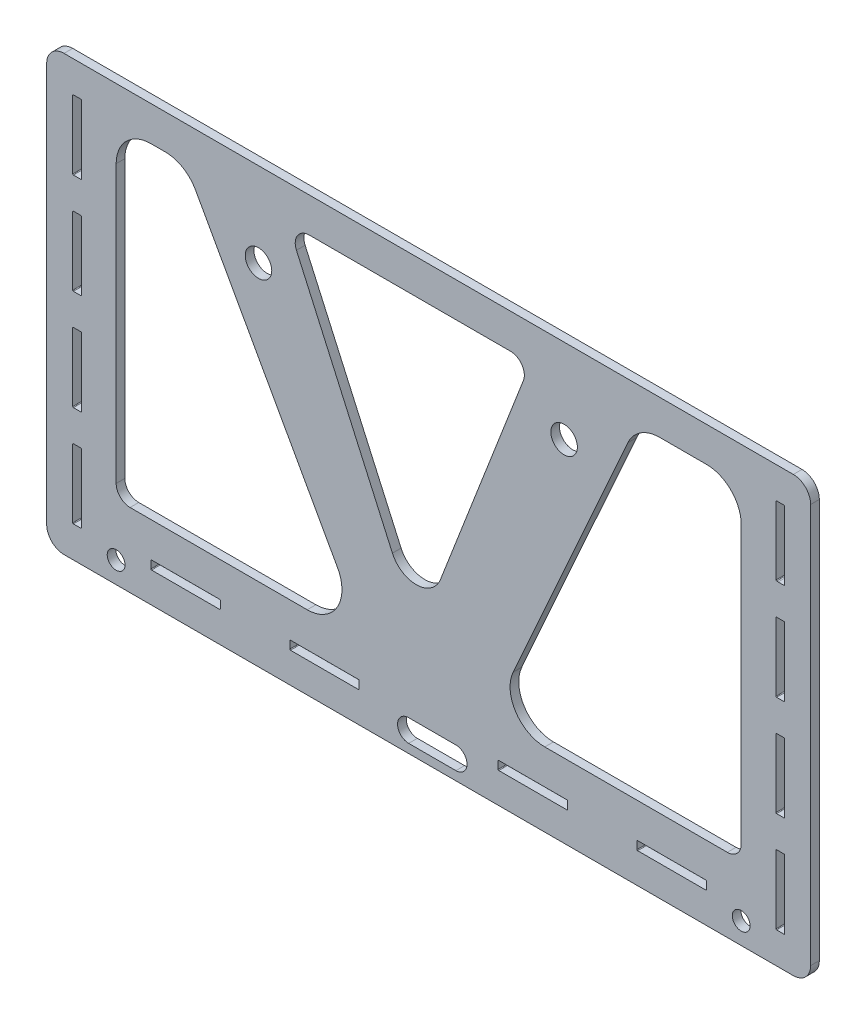
SolidWorks part; units mm, degrees
ref_plane "Front Plane" through (0, 0, 0) normal (0, 0, 1) x (1, 0, 0)
ref_plane "Top Plane" through (0, 0, 0) normal (0, 1, 0) x (1, 0, 0)
ref_plane "Right Plane" through (0, 0, 0) normal (1, 0, 0) x (0, 0, -1)
sketch "Model" plane through (0, 0, 0) normal (0, 0, 1) x (1, 0, 0)
  line L0 (402.4987, 280.7936) -> (432.8371, 358.964)
  line L1 (349.8266, 358.7257) -> (384.9258, 280.3469)
  line L2 (271.1967, 342.006) -> (271.1967, 366.898)
  line L3 (271.1967, 305.176) -> (271.1967, 330.068)
  line L4 (271.1967, 268.346) -> (271.1967, 293.238)
  line L5 (271.1967, 231.516) -> (271.1967, 256.408)
  line L6 (428.1012, 365.882) -> (354.463, 365.882)
  line L7 (270.9427, 367.152) -> (268.263, 367.152)
  line L8 (270.9427, 330.322) -> (268.263, 330.322)
  line L9 (270.9427, 293.492) -> (268.263, 293.492)
  line L10 (270.9427, 256.662) -> (268.263, 256.662)
  line L11 (283.8967, 251.9122) -> (283.8967, 353.182)
  line L12 (525.9968, 341.752) -> (525.4507, 341.752)
  line L13 (525.1967, 342.006) -> (525.1967, 366.898)
  line L14 (525.4507, 367.152) -> (528.1304, 367.152)
  line L15 (296.838, 234.1322) -> (321.73, 234.1322)
  line L16 (321.984, 233.8782) -> (321.984, 231.1985)
  line L17 (474.638, 234.1322) -> (499.53, 234.1322)
  line L18 (499.784, 233.8782) -> (499.784, 231.1985)
  line L19 (525.1967, 268.346) -> (525.1967, 293.238)
  line L20 (525.4507, 293.492) -> (528.1304, 293.492)
  line L21 (531.534, 378.582) -> (264.834, 378.582)
  line L22 (258.484, 372.232) -> (258.484, 226.182)
  line L23 (264.834, 219.832) -> (531.534, 219.832)
  line L24 (537.884, 226.182) -> (537.884, 372.232)
  line L25 (525.1967, 231.516) -> (525.1967, 256.408)
  line L26 (423.838, 234.1322) -> (448.73, 234.1322)
  line L27 (448.984, 233.8782) -> (448.984, 231.1985)
  line L28 (372.784, 233.8782) -> (372.784, 231.1985)
  line L29 (347.638, 234.1322) -> (372.53, 234.1322)
  line L30 (525.1967, 305.176) -> (525.1967, 330.068)
  line L31 (525.4507, 330.322) -> (528.1304, 330.322)
  line L32 (507.4167, 246.8322) -> (440.6634, 246.8322)
  line L33 (525.9968, 341.752) -> (528.1288, 341.7388)
  line L34 (528.1304, 231.262) -> (525.4507, 231.262)
  line L35 (528.3844, 231.516) -> (528.3844, 256.408)
  line L36 (528.3844, 341.9928) -> (528.3844, 366.898)
  line L37 (528.1304, 304.922) -> (525.4507, 304.922)
  line L38 (528.3844, 305.176) -> (528.3844, 330.068)
  line L39 (525.4507, 256.662) -> (528.1304, 256.662)
  line L40 (528.1304, 268.092) -> (525.4507, 268.092)
  line L41 (528.3844, 268.346) -> (528.3844, 293.238)
  line L42 (321.73, 230.9445) -> (296.838, 230.9445)
  line L43 (268.263, 341.752) -> (270.9427, 341.752)
  line L44 (268.009, 342.006) -> (268.009, 366.898)
  line L45 (268.263, 304.922) -> (270.9427, 304.922)
  line L46 (268.009, 305.176) -> (268.009, 330.068)
  line L47 (268.263, 268.092) -> (270.9427, 268.092)
  line L48 (268.009, 268.346) -> (268.009, 293.238)
  line L49 (268.263, 231.262) -> (270.9427, 231.262)
  line L50 (268.009, 231.516) -> (268.009, 256.408)
  line L51 (499.53, 230.9445) -> (474.638, 230.9445)
  line L52 (474.384, 231.1985) -> (474.384, 233.8782)
  line L53 (423.584, 231.1985) -> (423.584, 233.8782)
  line L54 (448.73, 230.9445) -> (423.838, 230.9445)
  line L55 (372.53, 230.9445) -> (347.638, 230.9445)
  line L56 (347.384, 231.1985) -> (347.384, 233.8782)
  line L57 (296.584, 231.1985) -> (296.584, 233.8782)
  line L58 (390.8786, 231.1985) -> (408.1506, 231.1985)
  line L59 (408.1506, 223.0705) -> (390.8786, 223.0705)
  line L60 (301.8185, 365.882) -> (296.5967, 365.882)
  line L61 (364.8742, 265.6928) -> (312.9242, 359.3426)
  line L62 (353.7685, 246.8322) -> (288.9767, 246.8322)
  line L63 (471.0331, 358.3748) -> (429.0735, 264.725)
  line L64 (499.7967, 365.882) -> (482.623, 365.882)
  line L65 (512.4967, 353.182) -> (512.4967, 251.9122)
  arc A0 (432.8371, 358.964) -> (428.1012, 365.882) centre (428.1012, 360.802) ccw
  arc A1 (384.9258, 280.3469) -> (402.4987, 280.7936) centre (393.619, 284.2398) ccw
  arc A2 (354.463, 365.882) -> (349.8266, 358.7257) centre (354.463, 360.802) ccw
  arc A3 (271.1967, 366.898) -> (270.9427, 367.152) centre (270.9427, 366.898) ccw
  arc A4 (270.9427, 341.752) -> (271.1967, 342.006) centre (270.9427, 342.006) ccw
  arc A5 (271.1967, 330.068) -> (270.9427, 330.322) centre (270.9427, 330.068) ccw
  arc A6 (270.9427, 304.922) -> (271.1967, 305.176) centre (270.9427, 305.176) ccw
  arc A7 (271.1967, 293.238) -> (270.9427, 293.492) centre (270.9427, 293.238) ccw
  arc A8 (270.9427, 268.092) -> (271.1967, 268.346) centre (270.9427, 268.346) ccw
  arc A9 (271.1967, 256.408) -> (270.9427, 256.662) centre (270.9427, 256.408) ccw
  arc A10 (270.9427, 231.262) -> (271.1967, 231.516) centre (270.9427, 231.516) ccw
  arc A11 (283.8967, 251.9122) -> (288.9767, 246.8322) centre (288.9767, 251.9122) ccw
  arc A12 (525.1967, 342.006) -> (525.4507, 341.752) centre (525.4507, 342.006) ccw
  arc A13 (525.4507, 367.152) -> (525.1967, 366.898) centre (525.4507, 366.898) ccw
  arc A14 (296.838, 234.1322) -> (296.584, 233.8782) centre (296.838, 233.8782) ccw
  arc A15 (321.984, 233.8782) -> (321.73, 234.1322) centre (321.73, 233.8782) ccw
  arc A16 (474.638, 234.1322) -> (474.384, 233.8782) centre (474.638, 233.8782) ccw
  arc A17 (499.784, 233.8782) -> (499.53, 234.1322) centre (499.53, 233.8782) ccw
  arc A18 (525.1967, 268.346) -> (525.4507, 268.092) centre (525.4507, 268.346) ccw
  arc A19 (525.4507, 293.492) -> (525.1967, 293.238) centre (525.4507, 293.238) ccw
  arc A20 (264.834, 378.582) -> (258.484, 372.232) centre (264.834, 372.232) ccw
  arc A21 (258.484, 226.182) -> (264.834, 219.832) centre (264.834, 226.182) ccw
  arc A22 (531.534, 219.832) -> (537.884, 226.182) centre (531.534, 226.182) ccw
  arc A23 (537.884, 372.232) -> (531.534, 378.582) centre (531.534, 372.232) ccw
  arc A24 (525.1967, 231.516) -> (525.4507, 231.262) centre (525.4507, 231.516) ccw
  arc A25 (423.838, 234.1322) -> (423.584, 233.8782) centre (423.838, 233.8782) ccw
  arc A26 (448.984, 233.8782) -> (448.73, 234.1322) centre (448.73, 233.8782) ccw
  arc A27 (347.638, 234.1322) -> (347.384, 233.8782) centre (347.638, 233.8782) ccw
  arc A28 (372.784, 233.8782) -> (372.53, 234.1322) centre (372.53, 233.8782) ccw
  arc A29 (525.1967, 305.176) -> (525.4507, 304.922) centre (525.4507, 305.176) ccw
  arc A30 (525.4507, 330.322) -> (525.1967, 330.068) centre (525.4507, 330.068) ccw
  arc A31 (507.4167, 246.8322) -> (512.4967, 251.9122) centre (507.4167, 251.9122) ccw
  arc A32 (528.1304, 231.262) -> (528.3844, 231.516) centre (528.1304, 231.516) ccw
  arc A33 (528.1288, 341.7388) -> (528.3844, 341.9928) centre (528.1304, 341.9928) ccw
  arc A34 (528.3844, 366.898) -> (528.1304, 367.152) centre (528.1304, 366.898) ccw
  arc A35 (528.3844, 330.068) -> (528.1304, 330.322) centre (528.1304, 330.068) ccw
  arc A36 (528.1304, 304.922) -> (528.3844, 305.176) centre (528.1304, 305.176) ccw
  arc A37 (525.4507, 256.662) -> (525.1967, 256.408) centre (525.4507, 256.408) ccw
  arc A38 (528.1304, 268.092) -> (528.3844, 268.346) centre (528.1304, 268.346) ccw
  arc A39 (528.3844, 293.238) -> (528.1304, 293.492) centre (528.1304, 293.238) ccw
  arc A40 (528.3844, 256.408) -> (528.1304, 256.662) centre (528.1304, 256.408) ccw
  arc A41 (321.73, 230.9445) -> (321.984, 231.1985) centre (321.73, 231.1985) ccw
  arc A42 (268.263, 367.152) -> (268.009, 366.898) centre (268.263, 366.898) ccw
  arc A43 (268.009, 342.006) -> (268.263, 341.752) centre (268.263, 342.006) ccw
  arc A44 (268.009, 305.176) -> (268.263, 304.922) centre (268.263, 305.176) ccw
  arc A45 (268.263, 330.322) -> (268.009, 330.068) centre (268.263, 330.068) ccw
  arc A46 (268.009, 268.346) -> (268.263, 268.092) centre (268.263, 268.346) ccw
  arc A47 (268.263, 293.492) -> (268.009, 293.238) centre (268.263, 293.238) ccw
  arc A48 (268.263, 256.662) -> (268.009, 256.408) centre (268.263, 256.408) ccw
  arc A49 (268.009, 231.516) -> (268.263, 231.262) centre (268.263, 231.516) ccw
  arc A50 (499.53, 230.9445) -> (499.784, 231.1985) centre (499.53, 231.1985) ccw
  arc A51 (474.384, 231.1985) -> (474.638, 230.9445) centre (474.638, 231.1985) ccw
  arc A52 (423.584, 231.1985) -> (423.838, 230.9445) centre (423.838, 231.1985) ccw
  arc A53 (448.73, 230.9445) -> (448.984, 231.1985) centre (448.73, 231.1985) ccw
  arc A54 (372.53, 230.9445) -> (372.784, 231.1985) centre (372.53, 231.1985) ccw
  arc A55 (347.384, 231.1985) -> (347.638, 230.9445) centre (347.638, 231.1985) ccw
  arc A56 (296.584, 231.1985) -> (296.838, 230.9445) centre (296.838, 231.1985) ccw
  arc A57 (390.8786, 231.1985) -> (390.8786, 223.0705) centre (390.8786, 227.1345) ccw
  arc A58 (408.1506, 223.0705) -> (408.1506, 231.1985) centre (408.1506, 227.1345) ccw
  arc A59 (312.9242, 359.3426) -> (301.8185, 365.882) centre (301.8185, 353.182) ccw
  arc A60 (429.0735, 264.725) -> (440.6634, 246.8322) centre (440.6634, 259.5322) ccw
  arc A61 (353.7685, 246.8322) -> (364.8742, 265.6928) centre (353.7685, 259.5322) ccw
  arc A62 (296.5967, 365.882) -> (283.8967, 353.182) centre (296.5967, 353.182) ccw
  arc A63 (482.623, 365.882) -> (471.0331, 358.3748) centre (482.623, 353.182) ccw
  circle A64 centre (512.484, 227.6806) radius 3.2639
  circle A65 centre (283.884, 227.6806) radius 3.2639
  arc A66 (512.4967, 353.182) -> (499.7967, 365.882) centre (499.7967, 353.182) ccw
  circle A67 centre (335.954, 347.7273) radius 4.8514
  circle A68 centre (447.714, 347.7273) radius 4.8514
extrude "Boss-Extrude1" add sketch "Model" along normal blind 3.175 contours L2 A3 L7 A42 L44 A43 L43 A4 | L0 A0 L6 A2 L1 A1 | L4 A7 L9 A47 L48 A46 L47 A8 | L3 A5 L8 A45 L46 A44 L45 A6 | L15 A15 L16 A41 L42 A56 L57 A14 | L11 A62 L60 A59 L61 A61 L62 A11 | L5 A9 L10 A48 L50 A49 L49 A10 | L19 A19 L20 A39 L41 A38 L40 A18 | L17 A17 L18 A50 L51 A51 L52 A16 | L26 A26 L27 A53 L54 A52 L53 A25 | L25 A37 L39 A40 L35 A32 L34 A24 | L21 A20 L22 A21 L23 A22 L24 A23 | L32 A60 L63 A63 L64 A66 L65 A31 | L30 A30 L31 A35 L38 A36 L37 A29 | L28 A54 L55 A55 L56 A27 L29 A28 | L58 A58 L59 A57 | A68 | A67 | A65 | A64 | L12 A12 L13 A13 L14 A34 L36 A33 L33
